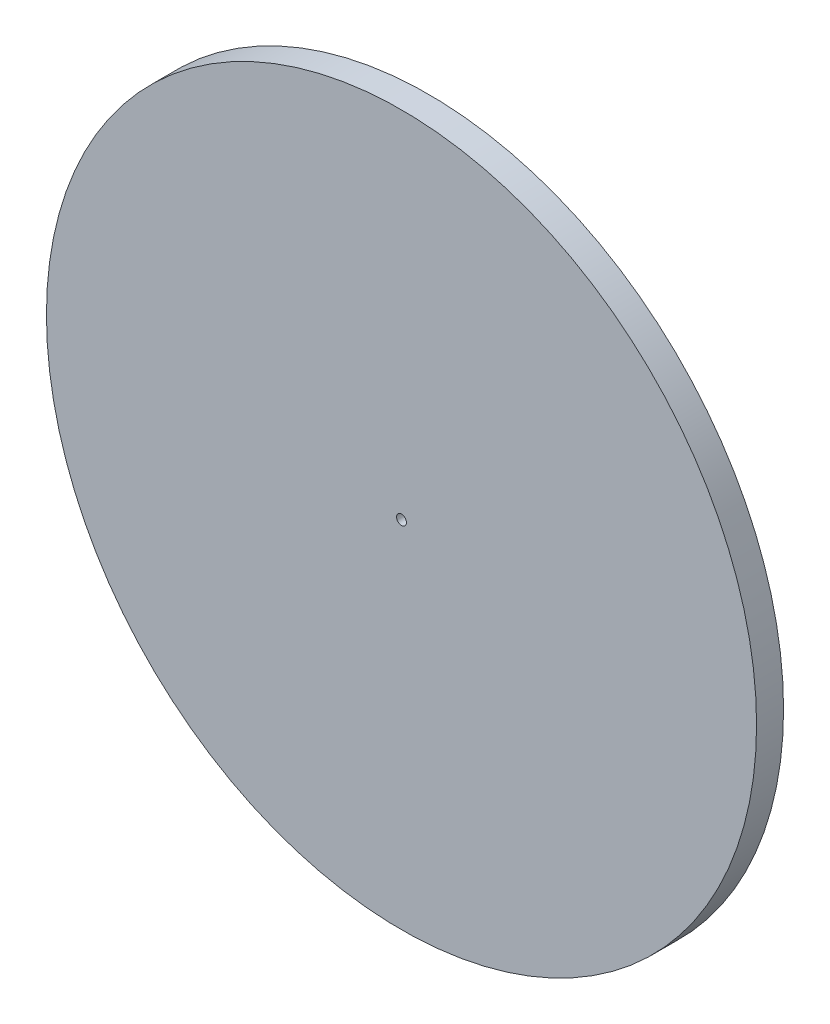
SolidWorks part; units mm, degrees
material "Pine"
ref_plane "Front Plane" through (0, 0, 0) normal (0, 0, 1) x (1, 0, 0)
ref_plane "Top Plane" through (0, 0, 0) normal (0, 1, 0) x (1, 0, 0)
ref_plane "Right Plane" through (0, 0, 0) normal (1, 0, 0) x (0, 0, -1)
sketch "Sketch2" plane through (0, 0, 0) normal (0, 0, 1) x (1, 0, 0)
  circle A0 centre (0, 0) radius 250
  circle A1 centre (0, 0) radius 3.5
  dimension "D1" = 7
  dimension "D2" = 500
extrude "Boss-Extrude1" add sketch "Sketch2" along normal mid plane 19
sketch "Sketch3" plane through (0, 0, -9.5) normal (0, 0, -1) x (-1, 0, 0)
  circle A0 centre (0, 0) radius 31
  dimension "D1" = 62
extrude "Cut-Extrude1" cut sketch "Sketch3" against normal blind 9
